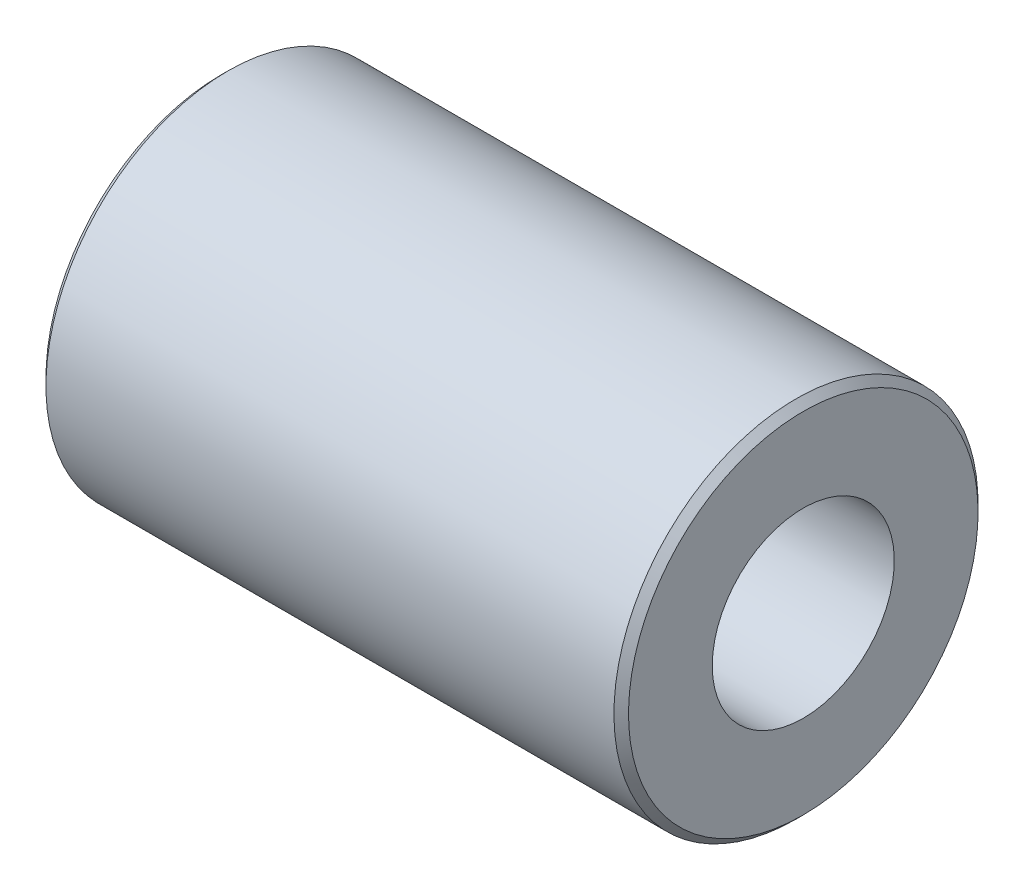
SolidWorks part; units mm, degrees
material "6061 合金"
ref_plane "前视基准面" through (0, 0, 0) normal (0, 0, 1) x (1, 0, 0)
ref_plane "上视基准面" through (0, 0, 0) normal (0, 1, 0) x (1, 0, 0)
ref_plane "右视基准面" through (0, 0, 0) normal (1, 0, 0) x (0, 0, -1)
sketch "草图1" plane through (0, 0, 0) normal (0, 0, 1) x (1, 0, 0)
  line L0 (-4, 0) -> (4, 0) construction
  line L1 (4, 0) -> (4, 2.5)
  line L2 (4, 2.5) -> (-4, 2.5)
  line L3 (-4, 2.5) -> (-4, 0)
  line L4 (4, 0) -> (-4, 0)
  point P4 (0, 0)
  dimension "D1" = 8
  dimension "D2" = 5
revolve "旋转1" add sketch "草图1" angle 360 about L0
hole_wizard "螺纹孔" positions "草图2" profile "草图3" tap size "M2" standard "GB"
sketch "草图2" plane through (-4, 0, 0) normal (-1, 0, 0) x (0, 0, 1)
  point P0 (0, 0)
sketch "草图3" plane through (-4, 0, 0) normal (0, 1, 0) x (0, 0, 1)
  line L0 (0, 0) -> (0, 10.7511)
  line L1 (0, 10.7511) -> (1.25, 10)
  line L2 (1.25, 10) -> (1.25, 0)
  line L5 (1.25, 0) -> (0, 0)
  line L10 (0, 10.7511) -> (-1.25, 10) construction
  line L11 (0, -6.35) -> (0, 107.95) construction
  dimension "螺纹孔钻头直径" = 2.5
  dimension "螺纹孔钻头深度" = 10
  dimension "导头角度" = 118
cosmetic thread "孔螺蚊线1" parameters "D1"=6, "D2"=2.9
mirror "镜向1" about plane through (0, 0, 0) normal (1, 0, 0) of "螺纹孔"
cosmetic thread "孔螺蚊线2" parameters "D1"=6, "D2"=2.9
chamfer "倒角1" distance 0.1 angle 45 2 edges at (4, -2.5, 0) (-4, -2.5, 0)
